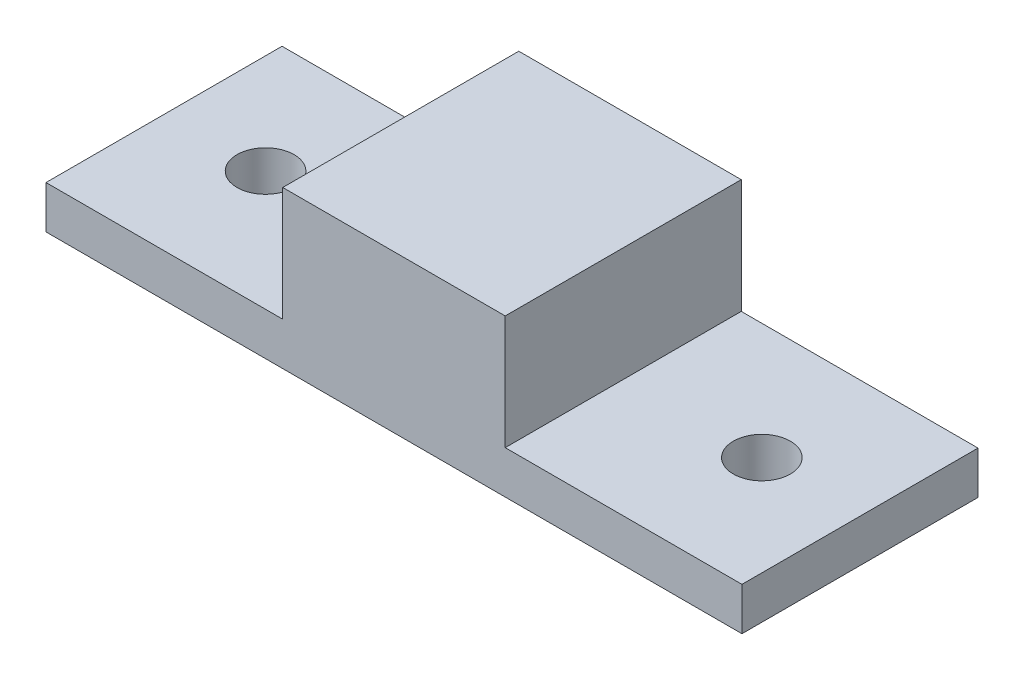
SolidWorks part; units mm, degrees
ref_plane "Front Plane" through (0, 0, 0) normal (0, 0, 1) x (1, 0, 0)
ref_plane "Top Plane" through (0, 0, 0) normal (0, 1, 0) x (1, 0, 0)
ref_plane "Right Plane" through (0, 0, 0) normal (1, 0, 0) x (0, 0, -1)
sketch "Sketch1" plane through (0, 0, 0) normal (0, 1, 0) x (1, 0, 0)
  line L1 (0, 0) -> (61.976, 0)
  line L2 (0, 0) -> (0, 21.0193)
  line L3 (0, 21.0193) -> (61.976, 21.0193)
  line L4 (61.976, 0) -> (61.976, 21.0193)
  circle A0 centre (8.89, 10.661) radius 2.54
  circle A1 centre (53.086, 10.661) radius 2.54
  dimension "D5" = 5.08
  dimension "D6" = 5.08
  dimension "D1" = 61.976
  dimension "D2" = 21.0193
  dimension "D3" = 8.89
  dimension "D4" = 8.89
extrude "Boss-Extrude1" add sketch "Sketch1" along normal blind 3.81
sketch "Sketch2" plane through (0, 3.81, 0) normal (0, 1, 0) x (1, 0, 0)
  line L0 (61.976, 21.0193) -> (0, 21.0193) construction
  line L1 (21.082, 21.0193) -> (40.894, 21.0193)
  line L2 (21.082, 21.0193) -> (21.082, 0)
  line L3 (21.082, 0) -> (40.894, 0)
  line L4 (40.894, 21.0193) -> (40.894, 0)
  line L5 (0, 0) -> (61.976, 0) construction
  line L6 (61.976, 0) -> (61.976, 21.0193) construction
  line L7 (0, 21.0193) -> (0, 0) construction
  dimension "D1" = 21.082
  dimension "D2" = 21.082
extrude "Boss-Extrude2" add sketch "Sketch2" along normal blind 10.16
